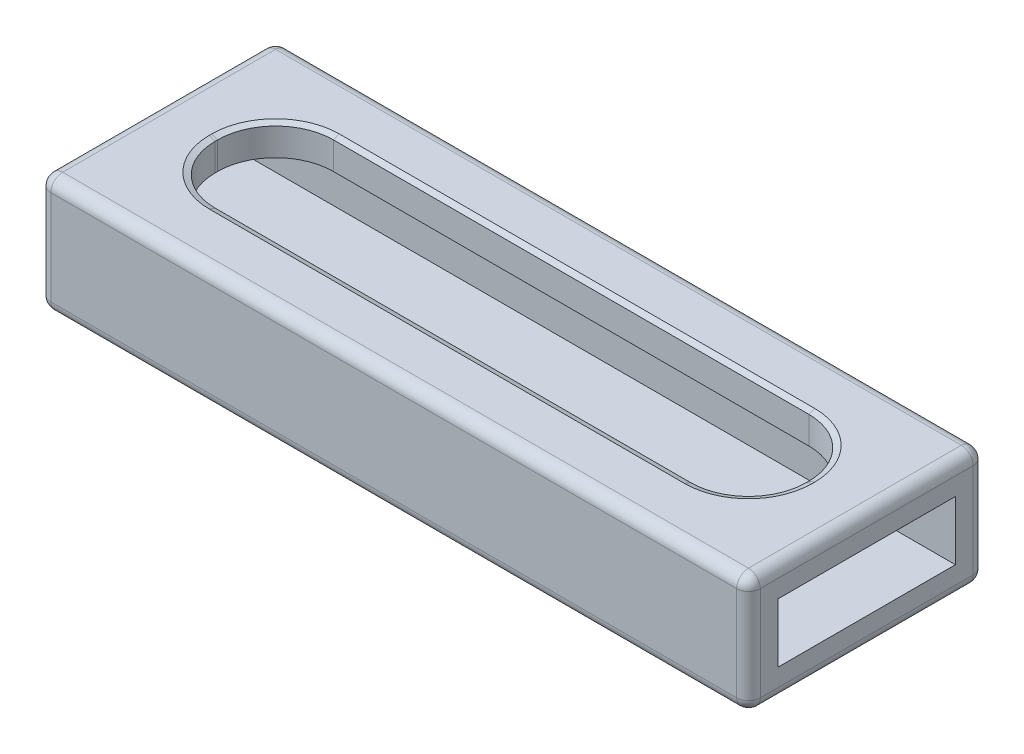
SolidWorks part; units mm, degrees
ref_plane "Front Plane" through (0, 0, 0) normal (0, 0, 1) x (1, 0, 0)
ref_plane "Top Plane" through (0, 0, 0) normal (0, 1, 0) x (1, 0, 0)
ref_plane "Right Plane" through (0, 0, 0) normal (1, 0, 0) x (0, 0, -1)
sketch "Sketch1" plane through (0, 0, 0) normal (0, 1, 0) x (1, 0, 0)
  line L1 (0, 0) -> (76.2, 0)
  line L2 (0, 0) -> (0, 25.4)
  line L3 (0, 25.4) -> (76.2, 25.4)
  line L4 (76.2, 0) -> (76.2, 25.4)
  dimension "D1" = 25.4
  dimension "D2" = 76.2
extrude "Boss-Extrude1" add sketch "Sketch1" along normal blind 12.7
sketch "Sketch2" plane through (76.2, 0, 0) normal (1, 0, 0) x (0, 0, -1)
  line L1 (3.175, 3.175) -> (22.225, 3.175)
  line L2 (3.175, 3.175) -> (3.175, 9.525)
  line L3 (3.175, 9.525) -> (22.225, 9.525)
  line L4 (22.225, 3.175) -> (22.225, 9.525)
  line L5 (0, 12.7) -> (0, 0) construction
  line L6 (0, 12.7) -> (25.4, 12.7) construction
  dimension "D1" = 19.05
  dimension "D2" = 3.175
  dimension "D3" = 6.35
  dimension "D4" = 3.175
extrude "Cut-Extrude1" cut sketch "Sketch2" against normal through all
sketch "Sketch3" plane through (0, 12.7, 0) normal (0, 1, 0) x (1, 0, 0)
  line L0 (76.2, 25.4) -> (0, 25.4) construction
  line L1 (12.573, 6.35) -> (63.627, 6.35)
  line L2 (6.35, 12.573) -> (6.35, 12.827)
  line L3 (12.573, 19.05) -> (63.627, 19.05)
  line L4 (69.85, 12.573) -> (69.85, 12.827)
  line L5 (0, 25.4) -> (0, 0) construction
  arc A0 (63.627, 19.05) -> (69.85, 12.827) centre (63.627, 12.827) cw
  arc A1 (69.85, 12.573) -> (63.627, 6.35) centre (63.627, 12.573) cw
  arc A2 (12.573, 6.35) -> (6.35, 12.573) centre (12.573, 12.573) cw
  arc A3 (6.35, 12.827) -> (12.573, 19.05) centre (12.573, 12.827) cw
  point P10 (69.85, 19.05)
  point P13 (69.85, 6.35)
  point P16 (6.35, 6.35)
  dimension "D5" = 6.223
  dimension "D1" = 63.5
  dimension "D2" = 6.35
  dimension "D3" = 12.7
  dimension "D4" = 6.35
extrude "Cut-Extrude2" cut sketch "Sketch3" against normal blind 3.175
fillet "Fillet1" radius 1.27 12 edges at (0, 6.35, 0) (76.2, 6.35, 0) (76.2, 6.35, -25.4) (0, 6.35, -25.4) (38.1, 0, 0) (76.2, 0, -12.7) (38.1, 0, -25.4) (0, 0, -12.7) (76.2, 12.7, -12.7) (38.1, 12.7, -25.4) (0, 12.7, -12.7) (38.1, 12.7, 0)
chamfer "Chamfer1" distance 0.635 angle 20 8 edges at (38.1, 12.7, -6.35) (68.0273, 12.7, -8.1727) (8.1727, 12.7, -8.1727) (69.85, 12.7, -12.7) (6.35, 12.7, -12.7) (68.0273, 12.7, -17.2273) (8.1727, 12.7, -17.2273) (38.1, 12.7, -19.05)
